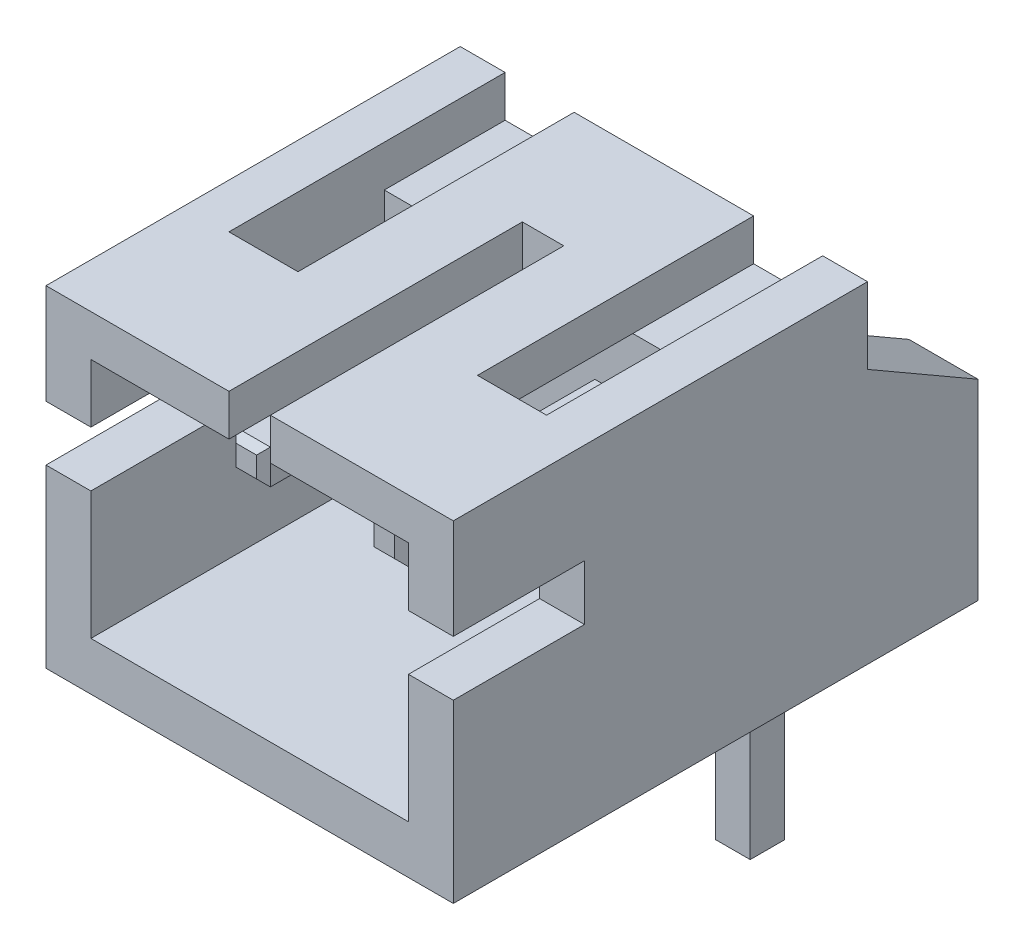
SolidWorks part; units mm, degrees
ref_plane "前视基准面" through (0, 0, 0) normal (0, 0, 1) x (1, 0, 0)
ref_plane "上视基准面" through (0, 0, 0) normal (0, 1, 0) x (1, 0, 0)
ref_plane "右视基准面" through (0, 0, 0) normal (1, 0, 0) x (0, 0, -1)
ref_plane "基准面4" through (0, -1.8, 0) normal (0, -1, 0) x (1, 0, 0)
sketch "草图1" plane through (0, -1.8, 0) normal (0, -1, 0) x (1, 0, 0)
  line L0 (-7.45, 8.95) -> (-7.45, 4.7)
  line L1 (-7.45, 4.7) -> (-8.05, 4.7)
  line L2 (-8.05, 4.7) -> (-8.05, 8.95)
  line L3 (-8.05, 8.95) -> (-10.7, 8.95)
  line L4 (-10.7, 8.95) -> (-10.7, 2.95)
  line L5 (-10.7, 2.95) -> (-10.05, 2.95)
  line L6 (-10.05, 2.95) -> (-10.05, 6.95)
  line L7 (-10.05, 6.95) -> (-9.05, 6.95)
  line L8 (-9.05, 6.95) -> (-9.05, 2.95)
  line L9 (-9.05, 2.95) -> (-6.45, 2.95)
  line L10 (-6.45, 2.95) -> (-6.45, 6.95)
  line L11 (-6.45, 6.95) -> (-5.45, 6.95)
  line L12 (-5.45, 6.95) -> (-5.45, 2.95)
  line L13 (-5.45, 2.95) -> (-4.8, 2.95)
  line L14 (-4.8, 2.95) -> (-4.8, 8.95)
  line L15 (-4.8, 8.95) -> (-7.45, 8.95)
extrude "凸台-拉伸1" add sketch "草图1" against normal blind 0.6
sketch "草图2" plane through (0, -1.8, 0) normal (0, -1, 0) x (1, 0, 0)
  line L0 (-10.7, 8.95) -> (-10.05, 8.95)
  line L1 (-10.05, 8.95) -> (-10.05, 4.7)
  line L2 (-10.05, 4.7) -> (-5.45, 4.7)
  line L3 (-5.45, 4.7) -> (-5.45, 8.95)
  line L4 (-5.45, 8.95) -> (-4.8, 8.95)
  line L5 (-4.8, 8.95) -> (-4.8, 2.95)
  line L6 (-4.8, 2.95) -> (-10.7, 2.95)
  line L7 (-10.7, 2.95) -> (-10.7, 8.95)
extrude "凸台-拉伸2" add sketch "草图2" along normal blind 3.5
sketch "草图3" plane through (0, -5.3, 0) normal (0, -1, 0) x (1, 0, 0)
  line L0 (-10.7, 2.95) -> (-10.7, 8.95)
  line L1 (-10.7, 8.95) -> (-4.8, 8.95)
  line L2 (-4.8, 8.95) -> (-4.8, 2.95)
  line L3 (-4.8, 2.95) -> (-10.7, 2.95)
extrude "凸台-拉伸3" add sketch "草图3" along normal blind 0.7
ref_plane "基准面5" through (0, 0, 2.45) normal (0, 0, -1) x (-1, 0, 0)
sketch "草图4" plane through (0, 0, 2.45) normal (0, 0, -1) x (-1, 0, 0)
  line L0 (8.5, -3.15) -> (8.5, -6)
  line L1 (8.5, -6) -> (9, -6)
  line L2 (9, -6) -> (9, -3.15)
  line L3 (9, -3.15) -> (8.5, -3.15)
extrude "凸台-拉伸4" add sketch "草图4" against normal up to next
sketch "草图5" plane through (0, -6, 0) normal (0, -1, 0) x (1, 0, 0)
  line L0 (-9, 2.95) -> (-8.5, 2.95)
  line L1 (-8.5, 2.95) -> (-8.5, 2.45)
  line L2 (-8.5, 2.45) -> (-9, 2.45)
  line L3 (-9, 2.45) -> (-9, 2.95)
extrude "凸台-拉伸5" add sketch "草图5" along normal blind 3.4
ref_plane "基准面6" through (0, 0, 2.95) normal (0, 0, 1) x (1, 0, 0)
sketch "草图7" plane through (0, 0, 2.45) normal (0, 0, -1) x (-1, 0, 0)
  line L0 (6.5, -3.15) -> (6.5, -6)
  line L1 (6.5, -6) -> (7, -6)
  line L2 (7, -6) -> (7, -3.15)
  line L3 (7, -3.15) -> (6.5, -3.15)
extrude "凸台-拉伸6" add sketch "草图7" against normal up to surface up to plane "基准面6"
sketch "草图8" plane through (0, -6, 0) normal (0, -1, 0) x (1, 0, 0)
  line L0 (-7, 2.95) -> (-6.5, 2.95)
  line L1 (-6.5, 2.95) -> (-6.5, 2.45)
  line L2 (-6.5, 2.45) -> (-7, 2.45)
  line L3 (-7, 2.45) -> (-7, 2.95)
extrude "凸台-拉伸7" add sketch "草图8" along normal blind 3.4
sketch "草图9" plane through (0, 0, 4.7) normal (0, 0, 1) x (1, 0, 0)
  line L0 (-5.45, -3.45) -> (-10.05, -3.45)
  line L1 (-10.05, -3.45) -> (-10.05, -5.3)
  line L2 (-10.05, -5.3) -> (-5.45, -5.3)
  line L3 (-5.45, -5.3) -> (-5.45, -3.45)
extrude "切除-拉伸1" cut sketch "草图9" against normal blind 0.6
sketch "草图10" plane through (-10.7, 0, 0) normal (-1, 0, 0) x (0, 0, 1)
  line L0 (8.95, -3.45) -> (8.95, -2.65)
  line L1 (8.95, -2.65) -> (7.05, -2.65)
  line L2 (7.05, -2.65) -> (7.05, -3.45)
  line L3 (7.05, -3.45) -> (8.95, -3.45)
extrude "切除-拉伸2" cut sketch "草图10" against normal up to next
sketch "草图11" plane through (-4.8, 0, 0) normal (1, 0, 0) x (0, 0, -1)
  line L0 (-8.95, -2.65) -> (-8.95, -3.45)
  line L1 (-8.95, -3.45) -> (-7.05, -3.45)
  line L2 (-7.05, -3.45) -> (-7.05, -2.65)
  line L3 (-7.05, -2.65) -> (-8.95, -2.65)
extrude "切除-拉伸3" cut sketch "草图11" against normal through all
sketch "草图12" plane through (0, 0, 2.95) normal (0, 0, -1) x (-1, 0, 0)
  line L0 (9.7, -6) -> (9.7, -2.3)
  line L1 (9.7, -2.3) -> (10.7, -2.3)
  line L2 (10.7, -2.3) -> (10.7, -6)
  line L3 (10.7, -6) -> (9.7, -6)
extrude "凸台-拉伸8" add sketch "草图12" along normal blind 1.6
sketch "草图13" plane through (0, 0, 2.95) normal (0, 0, -1) x (-1, 0, 0)
  line L0 (5.8, -2.3) -> (5.8, -6)
  line L1 (5.8, -6) -> (4.8, -6)
  line L2 (4.8, -6) -> (4.8, -2.3)
  line L3 (4.8, -2.3) -> (5.8, -2.3)
extrude "凸台-拉伸9" add sketch "草图13" along normal blind 1.6
sketch "草图14" plane through (0, 0, 4.7) normal (0, 0, 1) x (1, 0, 0)
  line L0 (-7, -2.65) -> (-6.5, -2.65)
  line L1 (-6.5, -2.65) -> (-6.5, -3.15)
  line L2 (-6.5, -3.15) -> (-7, -3.15)
  line L3 (-7, -3.15) -> (-7, -2.65)
extrude "凸台-拉伸10" add sketch "草图14" along normal blind 3.3
sketch "草图15" plane through (0, 0, 4.7) normal (0, 0, 1) x (1, 0, 0)
  line L0 (-9, -2.65) -> (-8.5, -2.65)
  line L1 (-8.5, -2.65) -> (-8.5, -3.15)
  line L2 (-8.5, -3.15) -> (-9, -3.15)
  line L3 (-9, -3.15) -> (-9, -2.65)
extrude "凸台-拉伸11" add sketch "草图15" along normal blind 3.3
draft "拔模1" type of draft neutral plane draft angle 45 faces to draft 1 face at (-7.75, -3.45, 4.4) neutral plane through (-7.45, -1.2, 4.7) neutral plane normal (0, 0, 1) parameters "D1"=45
draft "拔模2" type of draft neutral plane draft angle 30 faces to draft 2 face at (-5.3, -2.3, 2.15) face at (-10.2, -2.3, 2.15) neutral plane through (-5.45, -1.2, 2.95) neutral plane normal (0, 0, -1) parameters "D1"=30
fillet "圆角1" radius 0.4 2 edges at (-8.75, -3.15, 2.45) (-6.75, -3.15, 2.45)
chamfer "倒角1" distance 0.1 angle 45 16 edges at (-6.75, -9.4, 2.95) (-6.5, -9.4, 2.7) (-6.75, -9.4, 2.45) (-7, -9.4, 2.7) (-8.75, -9.4, 2.95) (-8.5, -9.4, 2.7) (-8.75, -9.4, 2.45) (-9, -9.4, 2.7) (-6.75, -2.65, 8) (-6.5, -2.9, 8) (-6.75, -3.15, 8) (-7, -2.9, 8) (-8.75, -2.65, 8) (-8.5, -2.9, 8) (-8.75, -3.15, 8) (-9, -2.9, 8)
